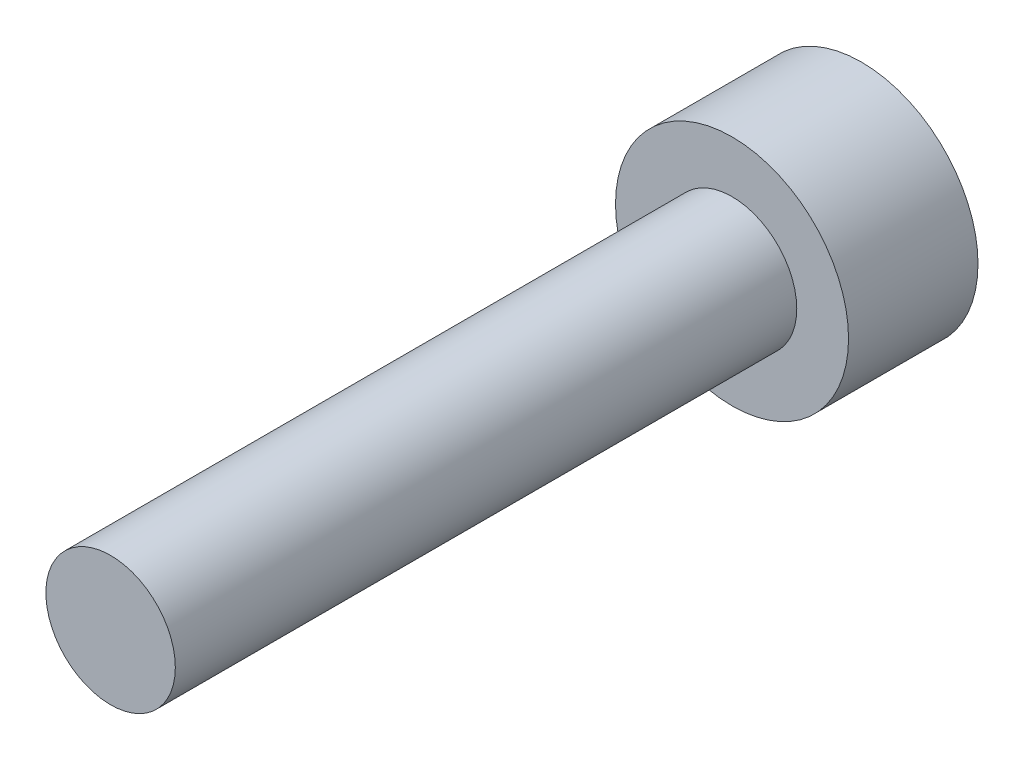
SolidWorks part; units mm, degrees
material "AISI 304"
ref_plane "前视基准面" through (0, 0, 0) normal (0, 0, 1) x (1, 0, 0)
ref_plane "上视基准面" through (0, 0, 0) normal (0, 1, 0) x (1, 0, 0)
ref_plane "右视基准面" through (0, 0, 0) normal (1, 0, 0) x (0, 0, -1)
sketch "草图1" plane through (0, 0, 0) normal (0, 0, 1) x (1, 0, 0)
  circle A0 centre (0, 0) radius 2.25
  dimension "D1" = 4.5
extrude "凸台-拉伸1" add sketch "草图1" along normal blind 2.5
sketch "草图2" plane through (0, 0, 2.5) normal (0, 0, 1) x (1, 0, 0)
  circle A0 centre (0, 0) radius 1.25
  dimension "D1" = 2.5
extrude "凸台-拉伸2" add sketch "草图2" along normal blind 12
cosmetic thread "装饰螺纹线1" parameters "D2"=2.013
sketch "草图3" plane through (0, 0, 0) normal (0, 0, -1) x (-1, 0, 0)
  line L1 (1.1547, 0) -> (0.5774, 1)
  line L2 (0.5774, 1) -> (-0.5774, 1)
  line L3 (-0.5774, 1) -> (-1.1547, 0)
  line L4 (-1.1547, 0) -> (-0.5774, -1)
  line L5 (-0.5774, -1) -> (0.5774, -1)
  line L6 (0.5774, -1) -> (1.1547, 0)
  circle A0 centre (0, 0) radius 1 construction
  dimension "D1" = 2
extrude "切除-拉伸1" cut sketch "草图3" against normal blind 1
